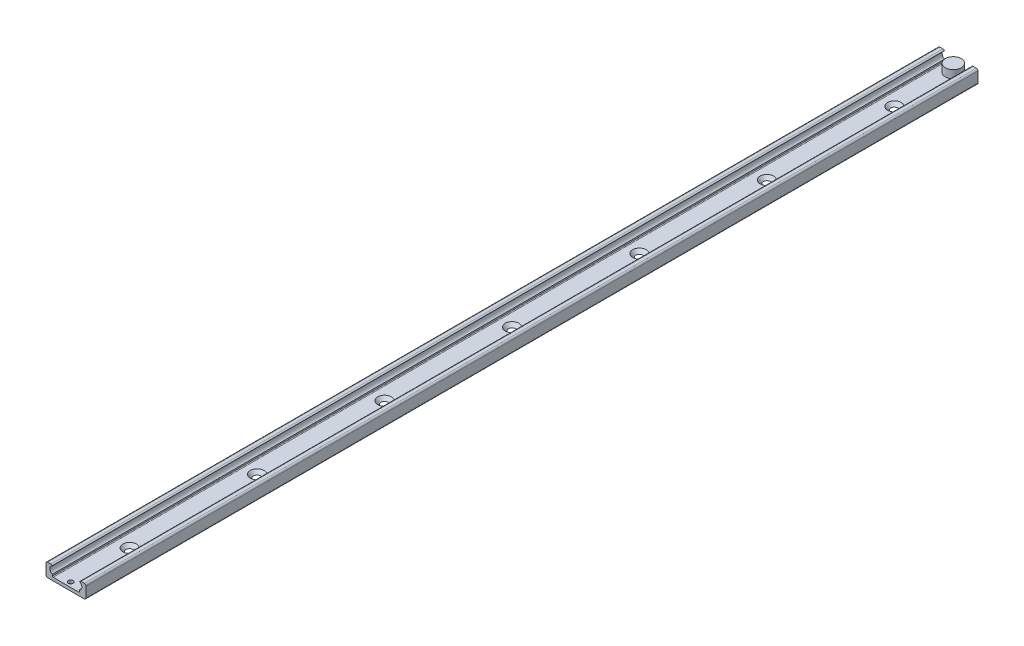
SolidWorks part; units mm, degrees
material "1060 合金"
ref_plane "正面" through (0, 0, 0) normal (0, 0, 1) x (1, 0, 0)
ref_plane "平面" through (0, 0, 0) normal (0, 1, 0) x (1, 0, 0)
ref_plane "右側面" through (0, 0, 0) normal (1, 0, 0) x (0, 0, -1)
ref_plane "平面1" through (0, 0, 720) normal (0, 0, 1) x (1, 0, 0)
sketch "ｽｹｯﾁ1" plane through (0, 0, 720) normal (0, 0, 1) x (1, 0, 0)
  line L0 (8.5, 3.4087) -> (8.5, 2)
  line L1 (8.5, 2) -> (-8.5, 2)
  line L2 (-8.5, 2) -> (-8.5, 3.4087)
  line L3 (-9.5, 8.5) -> (-12.5, 8.5)
  line L4 (-12.5, 8.5) -> (-12.5, 0)
  line L5 (-12.5, 0) -> (12.5, 0)
  line L6 (12.5, 0) -> (12.5, 8.5)
  line L7 (12.5, 8.5) -> (9.5, 8.5)
  arc A0 (8.6036, 7.9432) -> (8.5, 3.4087) centre (7.5, 5.7) cw
  arc A1 (-8.5, 3.4087) -> (-8.6036, 7.9432) centre (-7.5, 5.7) cw
  arc A2 (-8.6036, 7.9432) -> (-9.5, 8.5) centre (-9.5, 7.5) ccw
  arc A3 (9.5, 8.5) -> (8.6036, 7.9432) centre (9.5, 7.5) ccw
extrude "ﾎﾞｽ - 押し出し1" add sketch "ｽｹｯﾁ1" against normal blind 720
sketch "ｽｹｯﾁ3" plane through (0, 2, 0) normal (0, 1, 0) x (-1, 0, 0)
  circle A0 centre (0, 3) radius 5
extrude "ﾎﾞｽ - 押し出し3" add sketch "ｽｹｯﾁ3" along normal blind 5
hole_wizard "穴1" positions "ｽｹｯﾁ5" profile "ｽｹｯﾁ4" legacy
sketch "ｽｹｯﾁ5" plane through (0, 2, 0) normal (0, 1, 0) x (1, 0, 0)
  point P0 (0, -40)
  point P1 (0, -680)
  point P2 (0, -600)
  point P3 (0, -520)
  point P4 (0, -440)
  point P5 (0, -360)
  point P6 (0, -280)
  point P7 (0, -200)
  point P8 (0, -120)
sketch "ｽｹｯﾁ4" plane through (0, 2, 40) normal (1, 0, 0) x (0, 0, 1)
  line L0 (0, 0) -> (0, 2)
  line L1 (0, 2) -> (2.25, 2)
  line L2 (2.25, 2) -> (4.25, 0)
  line L3 (4.25, 0) -> (0, 0)
  line L4 (0, 110) -> (0, -10) construction
  dimension "副次直径" = 4.5
  dimension "深さ" = 2
  dimension "主要直径" = 8.5
fillet "ﾌｨﾚｯﾄ1" radius 0.5 2 edges at (-8.5, 2, 360) (8.5, 2, 360)
fillet "ﾌｨﾚｯﾄ2" radius 1 4 edges at (12.5, 0, 360) (12.5, 8.5, 360) (-12.5, 8.5, 360) (-12.5, 0, 360)
sketch "ｽｹｯﾁ6" plane through (0, 0, 720) normal (0, 0, 1) x (1, 0, 0)
  line L0 (-11.5, 0) -> (11.5, 0) construction
  line L1 (-14.2853, 0) -> (14.1042, 0)
  line L2 (-14.2853, 0) -> (-14.2853, 8.5)
  line L3 (-14.2853, 8.5) -> (14.1042, 8.5)
  line L4 (14.1042, 0) -> (14.1042, 8.5)
  line L5 (11.5, 8.5) -> (9.5, 8.5) construction
  dimension "D1" = 28.3895
extrude "ｶｯﾄ - 押し出し1" cut sketch "ｽｹｯﾁ6" against normal blind 160
sketch "ｽｹｯﾁ7" plane through (0, 2, 0) normal (0, 1, 0) x (1, 0, 0)
  line L0 (0, -560) -> (0, -557) construction
  line L1 (8, -560) -> (-8, -560) construction
  circle A0 centre (0, -557) radius 1.5
  dimension "D2" = 3
  dimension "D1" = 3
extrude "ｶｯﾄ - 押し出し2" cut sketch "ｽｹｯﾁ7" against normal through all
